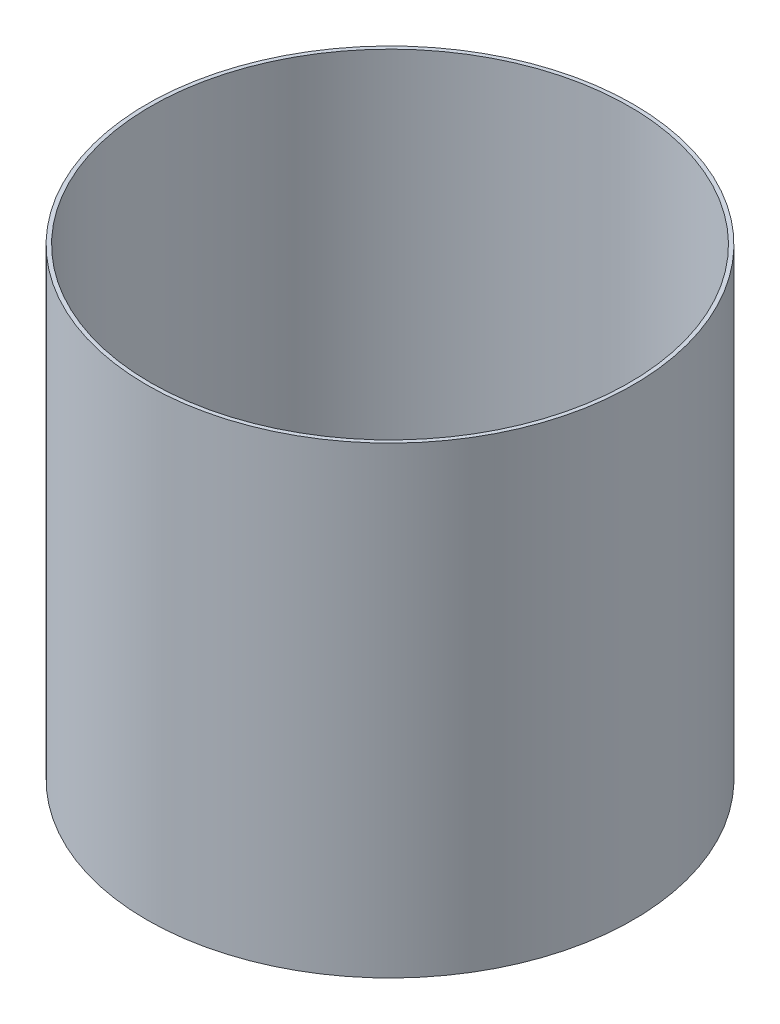
SolidWorks part; units mm, degrees
ref_plane "Front Plane" through (0, 0, 0) normal (0, 0, 1) x (1, 0, 0)
ref_plane "Top Plane" through (0, 0, 0) normal (0, 1, 0) x (1, 0, 0)
ref_plane "Right Plane" through (0, 0, 0) normal (1, 0, 0) x (0, 0, -1)
sketch "Sketch1" plane through (0, 0, 0) normal (0, 1, 0) x (1, 0, 0)
  circle A0 centre (0, 0) radius 63
  dimension "D1" = 126
extrude "Boss-Extrude1" add sketch "Sketch1" along normal blind 120
shell "Shell1" thickness 1
